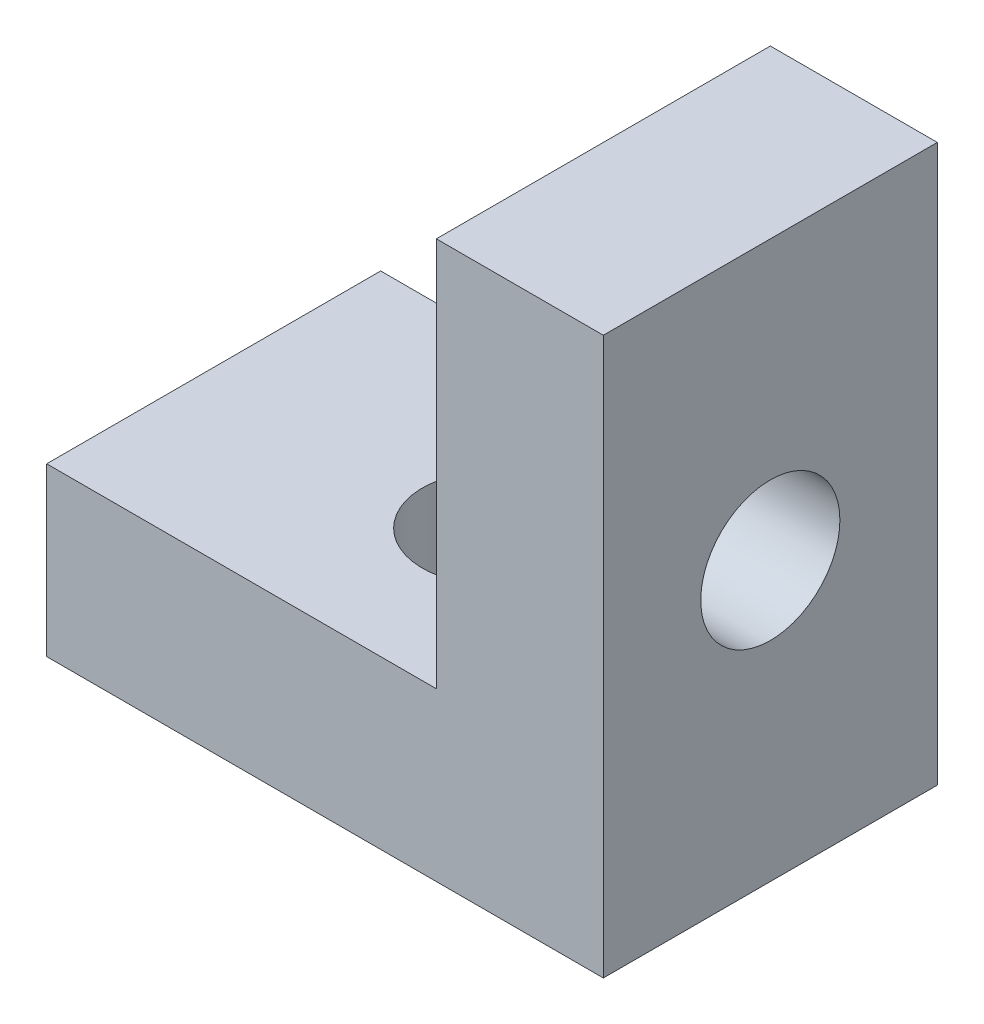
SolidWorks part; units mm, degrees
ref_plane "前视基准面" through (0, 0, 0) normal (0, 0, 1) x (1, 0, 0)
ref_plane "上视基准面" through (0, 0, 0) normal (0, 1, 0) x (1, 0, 0)
ref_plane "右视基准面" through (0, 0, 0) normal (1, 0, 0) x (0, 0, -1)
sketch "草图1" plane through (0, 0, 0) normal (0, 0, 1) x (1, 0, 0)
  line L0 (0, 0) -> (0, -3)
  line L1 (0, -3) -> (10, -3)
  line L2 (10, -3) -> (10, 7)
  line L3 (10, 7) -> (7, 7)
  line L4 (7, 7) -> (7, 0)
  line L5 (7, 0) -> (0, 0)
  dimension "D1" = 3
  dimension "D2" = 10
extrude "凸台-拉伸1" add sketch "草图1" along normal blind 6
sketch "草图2" plane through (0, -3, 0) normal (0, -1, 0) x (1, 0, 0)
  line L0 (0, 3) -> (10, 3) construction
  line L1 (0, 6) -> (0, 0) construction
  line L2 (10, 6) -> (10, 0) construction
  point P6 (5, 3)
sketch "草图3" plane through (10, 0, 0) normal (1, 0, 0) x (0, 0, -1)
  line L0 (-3, -3) -> (-3, 7) construction
  line L1 (-6, -3) -> (0, -3) construction
  line L2 (-6, 7) -> (0, 7) construction
  point P6 (-3, 2)
hole_wizard "M3 螺纹孔1" positions "草图4" profile "草图5" tap size "M3" standard "GB" end condition through all
sketch "草图4" plane through (0, -3, 0) normal (0, -1, 0) x (-1, 0, 0)
  point P0 (-5, -3)
sketch "草图5" plane through (5, -3, 3) normal (1, 0, 0) x (0, 0, -1)
  line L0 (0, 0) -> (0, 10)
  line L1 (0, 10) -> (1.25, 10)
  line L2 (1.25, 10) -> (1.25, 0)
  line L5 (1.25, 0) -> (0, 0)
  line L11 (0, -6.35) -> (0, 107.95) construction
  dimension "通孔螺纹孔钻头直径" = 2.5
  dimension "通孔螺纹孔钻头深度" = 10
cosmetic thread "孔螺蚊线1" parameters "D2"=3
hole_wizard "M3 螺纹孔2" positions "草图6" profile "草图7" tap size "M3" standard "GB" end condition through all
sketch "草图6" plane through (10, 0, 0) normal (1, 0, 0) x (0, 0, -1)
  point P0 (-3, 2)
sketch "草图7" plane through (10, 2, 3) normal (0, 1, 0) x (0, 0, -1)
  line L0 (0, 0) -> (0, 10)
  line L1 (0, 10) -> (1.25, 10)
  line L2 (1.25, 10) -> (1.25, 0)
  line L5 (1.25, 0) -> (0, 0)
  line L11 (0, -6.35) -> (0, 107.95) construction
  dimension "通孔螺纹孔钻头直径" = 2.5
  dimension "通孔螺纹孔钻头深度" = 10
cosmetic thread "孔螺蚊线2" parameters "D2"=3
